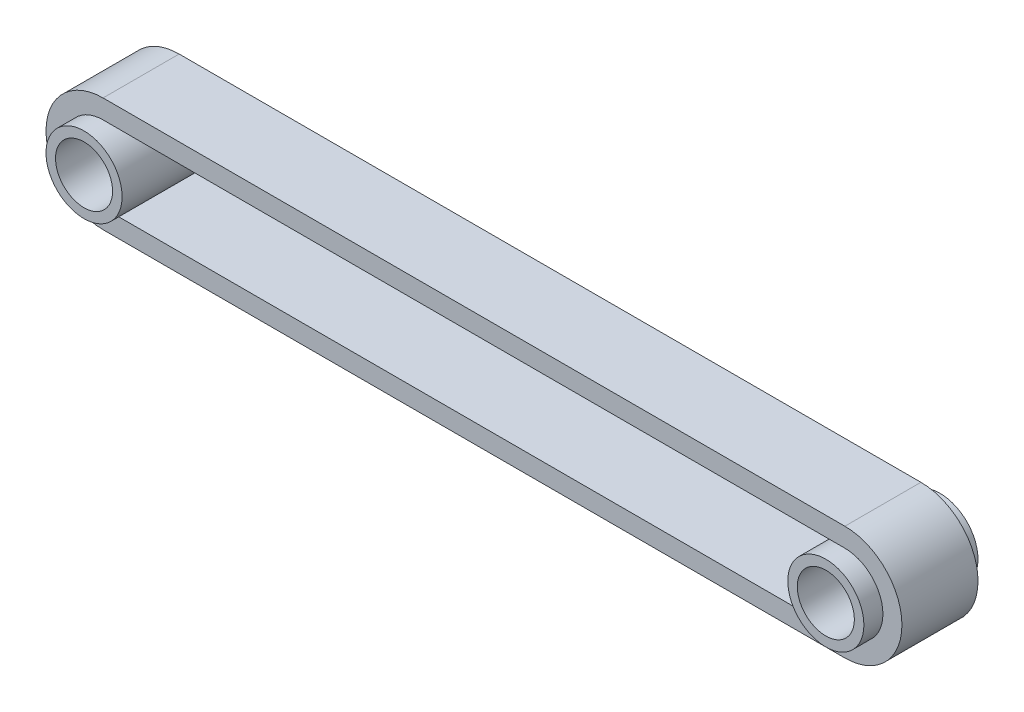
SolidWorks part; units mm, degrees
ref_plane "Front Plane" through (0, 0, 0) normal (0, 0, 1) x (1, 0, 0)
ref_plane "Top Plane" through (0, 0, 0) normal (0, 1, 0) x (1, 0, 0)
ref_plane "Right Plane" through (0, 0, 0) normal (1, 0, 0) x (0, 0, -1)
sketch "Sketch1" plane through (0, 0, 0) normal (0, 0, 1) x (1, 0, 0)
  circle A0 centre (0, 0) radius 15
  circle A1 centre (390, 0) radius 15
  circle A2 centre (0, 0) radius 20
  circle A3 centre (390, 0) radius 20
  dimension "D1" = 2
extrude "Boss-Extrude1" add sketch "Sketch1" along normal blind 60
sketch "Sketch2" plane through (0, 0, 60) normal (0, 0, 1) x (1, 0, 0)
  line L1 (0, -30) -> (390, -30)
  line L3 (390, 30) -> (0, 30)
  line L4 (0, 20) -> (390, 20)
  line L5 (0, -20) -> (390, -20)
  arc A0 (0, 20) -> (0, -20) centre (0, 0) ccw
  arc A1 (0, 30) -> (0, -30) centre (0, 0) ccw
  arc A2 (390, -30) -> (390, 30) centre (390, 0) ccw
  arc A3 (390, -20) -> (390, 20) centre (390, 0) ccw
extrude "Boss-Extrude2" add sketch "Sketch2" against normal blind 40 from offset 10
